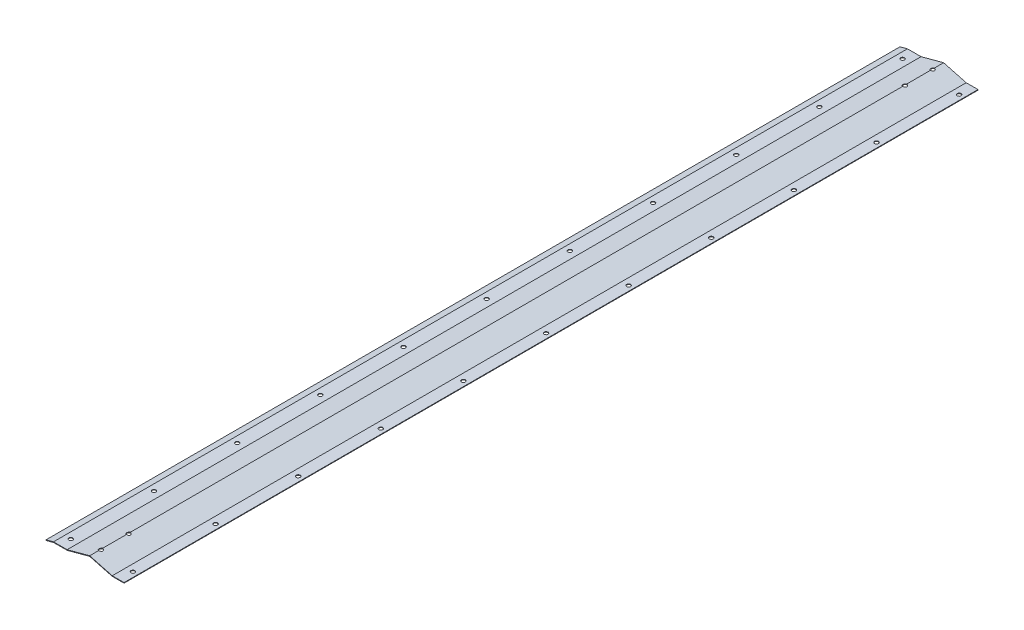
SolidWorks part; units mm, degrees
material "1023 Carbon Steel Sheet (SS)"
ref_plane "Front Plane" through (0, 0, 0) normal (0, 0, 1) x (1, 0, 0)
ref_plane "Top Plane" through (0, 0, 0) normal (0, 1, 0) x (1, 0, 0)
ref_plane "Right Plane" through (0, 0, 0) normal (1, 0, 0) x (0, 0, -1)
sketch "Sketch1" plane through (0, 0, 0) normal (0, 0, 1) x (1, 0, 0)
  line L0 (47860.381, 20322.1465) -> (47838.9541, 20322.1465)
  line L1 (47838.9541, 20322.1465) -> (47798.381, 20333.0168)
  line L2 (47798.381, 20333.0168) -> (47757.808, 20322.1465)
  line L3 (47757.808, 20322.1465) -> (47733.381, 20322.1465)
  line L7 (47733.1131, 20323.1465) -> (47757.6763, 20323.1465)
  line L8 (47757.6763, 20323.1465) -> (47798.381, 20334.052)
  line L9 (47798.381, 20334.052) -> (47839.0857, 20323.1465)
  line L10 (47839.0857, 20323.1465) -> (47860.381, 20323.1465)
  line L11 (47860.381, 20323.1465) -> (47860.381, 20322.1465)
  line L12 (47733.381, 20322.1465) -> (47719.8581, 20318.523)
  line L13 (47733.1131, 20323.1465) -> (47719.5901, 20319.523)
  line L14 (47719.5901, 20319.523) -> (47719.8581, 20318.523)
  dimension "D1" = 1
  dimension "D2" = 14
extrude "Boss-Extrude1" add sketch "Sketch1" along normal blind 1540
sketch "Sketch2" plane through (0, 20323.1465, 0) normal (0, 1, 0) x (1, 0, 0)
  line L0 (47798.381, -1540) -> (47798.381, 0) construction
  line L1 (47798.381, 0) -> (47757.6763, 0) construction
  circle A0 centre (47798.381, -20) radius 3.5
  circle A1 centre (47798.381, -70) radius 3.5
  circle A2 centre (47798.381, -1470) radius 3.5
  circle A3 centre (47798.381, -1520) radius 3.5
  dimension "D1" = 7
  dimension "D2" = 7
  dimension "D3" = 20
  dimension "D4" = 50
extrude "Cut-Extrude1" cut sketch "Sketch2" against normal through all both and the other way through all
sketch "Sketch3" plane through (0, 20323.1465, 0) normal (0, 1, 0) x (1, 0, 0)
  line L0 (47860.381, 0) -> (47839.0857, 0) construction
  line L1 (47860.381, -1540) -> (47860.381, 0) construction
  circle A0 centre (47851.381, -25) radius 3.5
  dimension "D1" = 7
  dimension "D2" = 25
  dimension "D3" = 9
extrude "Cut-Extrude2" cut sketch "Sketch3" against normal through all both and the other way through all
pattern_linear "LPattern1" count 11 spacing 149 along (0, 0, 1) of "Cut-Extrude2"
sketch "Sketch4" plane through (0, 20323.1465, 0) normal (0, 1, 0) x (1, 0, 0)
  line L0 (47798.381, -1540) -> (47798.381, -1523.5) construction
  line L1 (47757.6763, -1540) -> (47733.1131, -1540) construction
  circle A0 centre (47744.381, -1520) radius 3.5
  dimension "D1" = 7
  dimension "D2" = 54
  dimension "D3" = 20
extrude "Cut-Extrude3" cut sketch "Sketch4" against normal through all both and the other way through all
pattern_linear "LPattern2" count 11 spacing 150 along (0, 0, -1) of "Cut-Extrude3"
